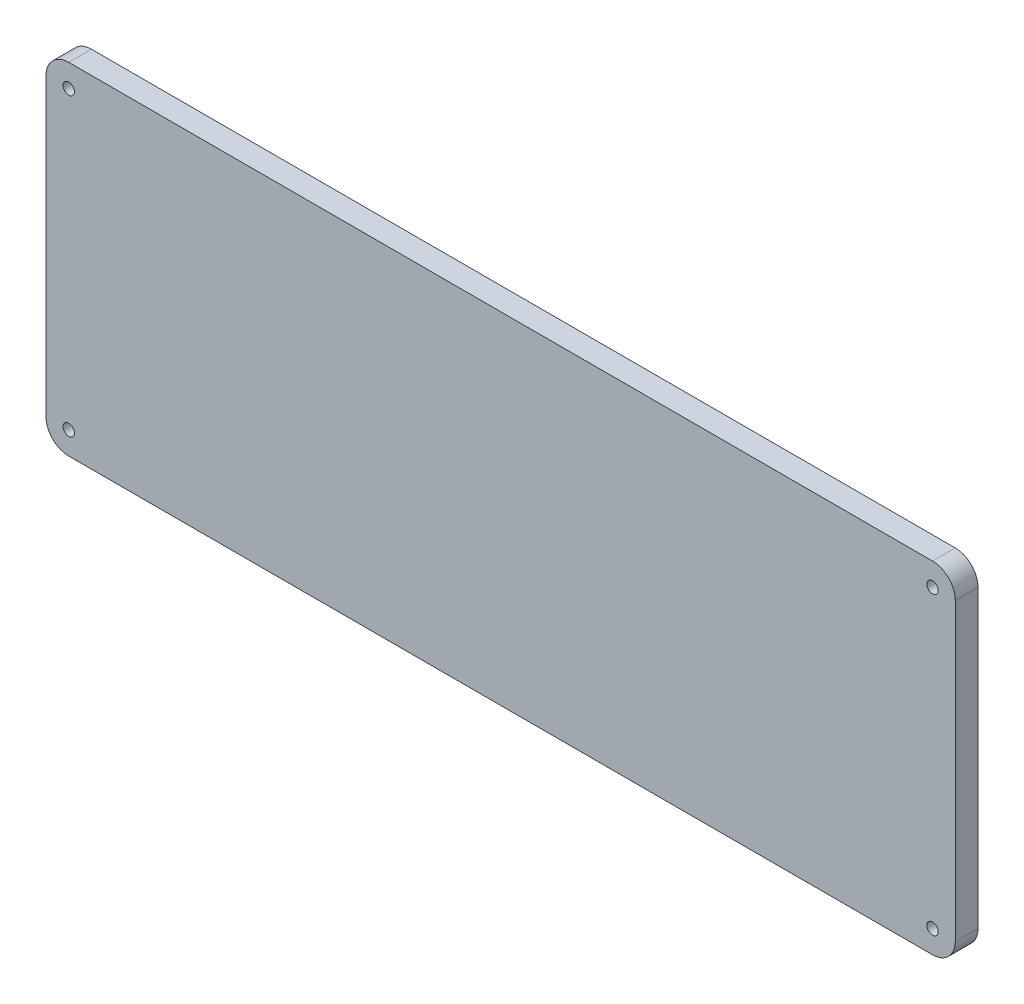
SolidWorks part; units mm, degrees
ref_plane "Front Plane" through (0, 0, 0) normal (0, 0, 1) x (1, 0, 0)
ref_plane "Top Plane" through (0, 0, 0) normal (0, 1, 0) x (1, 0, 0)
ref_plane "Right Plane" through (0, 0, 0) normal (1, 0, 0) x (0, 0, -1)
sketch "Sketch1" plane through (0, 0, 0) normal (0, 0, 1) x (1, 0, 0)
  line L0 (0, 0) -> (0, 45.2171) construction
  line L1 (-190, -75) -> (190, -75)
  line L2 (-200, -65) -> (-200, 65)
  line L3 (-190, 75) -> (190, 75)
  line L4 (200, -65) -> (200, 65)
  line L5 (-200, -75) -> (200, 75) construction
  line L6 (-200, 75) -> (200, -75) construction
  line L7 (0, 0) -> (-62.4213, 0) construction
  arc A0 (-190, -75) -> (-200, -65) centre (-190, -65) cw
  arc A1 (190, -75) -> (200, -65) centre (190, -65) ccw
  arc A2 (190, 75) -> (200, 65) centre (190, 65) cw
  arc A3 (-200, 65) -> (-190, 75) centre (-190, 65) cw
  circle A4 centre (-190, 65) radius 2.5
  circle A5 centre (-190, -65) radius 2.5
  circle A6 centre (190, -65) radius 2.5
  circle A7 centre (190, 65) radius 2.5
  point P0 (0, 0)
  dimension "D3" = 10
  dimension "D4" = 5
  dimension "D1" = 400
  dimension "D2" = 150
extrude "Boss-Extrude1" add sketch "Sketch1" along normal blind 10
